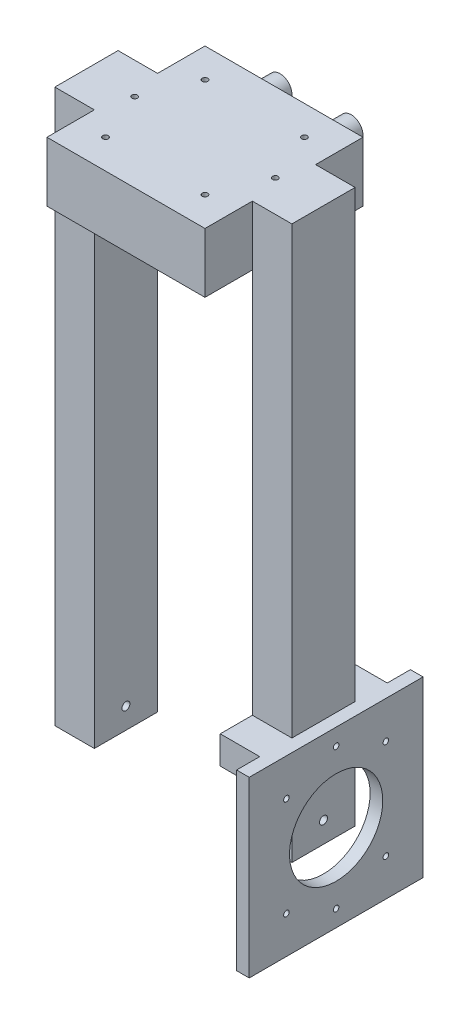
SolidWorks part; units mm, degrees
ref_plane "前视基准面" through (0, 0, 0) normal (0, 0, 1) x (1, 0, 0)
ref_plane "上视基准面" through (0, 0, 0) normal (0, 1, 0) x (1, 0, 0)
ref_plane "右视基准面" through (0, 0, 0) normal (1, 0, 0) x (0, 0, -1)
other "Configuration Table"
sketch "草图1" plane through (0, 0, 0) normal (0, 1, 0) x (1, 0, 0)
  line L1 (-75, 20) -> (75, 20)
  line L2 (-75, 20) -> (-75, -20)
  line L3 (-75, -20) -> (75, -20)
  line L4 (75, 20) -> (75, -20)
  line L5 (-75, 20) -> (75, -20) construction
  line L6 (-75, -20) -> (75, 20) construction
  point P0 (0, 0)
  dimension "D1" = 150
  dimension "D2" = 40
extrude "凸台-拉伸1" add sketch "草图1" along normal blind 350
sketch "草图7" plane through (0, 0, -20) normal (0, 0, -1) x (-1, 0, 0)
  line L1 (0, 0) -> (-50, 0)
  line L2 (0, 0) -> (0, 312.2326)
  line L3 (0, 312.2326) -> (-50, 312.2326)
  line L4 (-50, 0) -> (-50, 312.2326)
  dimension "D1" = 50
extrude "切除-拉伸3" cut sketch "草图7" against normal up to next
mirror "镜向2" about plane through (0, 0, 0) normal (1, 0, 0) of "切除-拉伸3"
sketch "草图8" plane through (-75, 0, 0) normal (-1, 0, 0) x (0, 0, 1)
  circle A0 centre (0, 13.2361) radius 2.5
  dimension "D1" = 5
extrude "切除-拉伸4" cut sketch "草图8" against normal up to next
mirror "镜向3" about plane through (0, 0, 0) normal (1, 0, 0) of "切除-拉伸4"
sketch "草图12" plane through (0, 0, 20) normal (0, 0, 1) x (1, 0, 0)
  line L0 (-75, 350) -> (75, 350) construction
  line L1 (-50, 312.2326) -> (50, 312.2326)
  line L2 (-50, 312.2326) -> (-50, 350)
  line L3 (-50, 350) -> (50, 350)
  line L4 (50, 312.2326) -> (50, 350)
extrude "凸台-拉伸2" add sketch "草图12" along normal mid plane 100 from surface at -20 starting at plane "前视基准面"
sketch "草图14" plane through (0, 350, 0) normal (0, 1, 0) x (1, 0, 0)
  circle A0 centre (0, 0) radius 44.5 construction
  circle A2 centre (-31.4663, -31.4663) radius 1.75
  circle A3 centre (-44.5, 0) radius 1.75
  circle A4 centre (-31.4663, 31.4663) radius 1.75
  circle A6 centre (31.4663, 31.4663) radius 1.75
  circle A7 centre (44.5, 0) radius 1.75
  circle A8 centre (31.4663, -31.4663) radius 1.75
  point P22 (0, 0)
  dimension "D1" = 89
extrude "切除-拉伸7" cut sketch "草图14" against normal blind 25
sketch "草图16" plane through (0, 0, -50) normal (0, 0, -1) x (-1, 0, 0)
  line L0 (-50, 331.1163) -> (50, 331.1163) construction
  line L1 (-50, 312.2326) -> (-50, 350) construction
  line L2 (50, 350) -> (50, 312.2326) construction
  line L3 (0, 331.1163) -> (0, 298.7734) construction
  circle A0 centre (-22.5, 331.1163) radius 7.5
  circle A1 centre (22.5, 331.1163) radius 7.5
  dimension "D1" = 15
  dimension "D2" = 45
extrude "凸台-拉伸3" add sketch "草图16" along normal blind 20
sketch "草图18" plane through (75, 0, 0) normal (1, 0, 0) x (0, 0, -1)
  line L1 (-55, 68.2361) -> (55, 68.2361)
  line L2 (-55, 68.2361) -> (-55, -41.7639)
  line L3 (-55, -41.7639) -> (55, -41.7639)
  line L4 (55, 68.2361) -> (55, -41.7639)
  line L5 (-55, 68.2361) -> (55, -41.7639) construction
  line L6 (-55, -41.7639) -> (55, 68.2361) construction
  point P0 (0, 13.2361)
  dimension "D1" = 110
extrude "凸台-拉伸4" add sketch "草图18" along normal blind 8
sketch "草图19" plane through (83, 0, 0) normal (1, 0, 0) x (0, 0, -1)
  circle A0 centre (0, 13.2361) radius 44.5 construction
  circle A1 centre (0, -31.2639) radius 1.75
  circle A2 centre (-31.4663, -18.2301) radius 1.75
  circle A4 centre (-31.4663, 44.7024) radius 1.75
  circle A5 centre (0, 57.7361) radius 1.75
  circle A6 centre (31.4663, 44.7024) radius 1.75
  circle A8 centre (31.4663, -18.2301) radius 1.75
  circle A9 centre (44.5, 13.2361) radius 1.75 [skipped]
  circle A10 centre (-44.5, 13.2361) radius 1.75 [skipped]
  point P21 (0, 13.2361)
  dimension "D1" = 89
  dimension "D2" = 3.5
  dimension "D3" = 8
extrude "切除-拉伸8" cut sketch "草图19" against normal blind 8
sketch "草图20" plane through (83, 0, 0) normal (1, 0, 0) x (0, 0, -1)
  circle A0 centre (0, 13.2361) radius 29.5
  dimension "D1" = 59
extrude "切除-拉伸9" cut sketch "草图20" against normal blind 8
sketch "草图21" plane through (75, 0, 0) normal (-1, 0, 0) x (0, 0, 1)
  line L1 (-40.3474, 50.5173) -> (-20, 50.5173)
  line L2 (-40.3474, 50.5173) -> (-40.3474, 68.2361)
  line L3 (-40.3474, 68.2361) -> (-20, 68.2361)
  line L4 (-20, 50.5173) -> (-20, 68.2361)
extrude "凸台-拉伸5" add sketch "草图21" along normal up to surface (25 mm away) up to face at (50, 13.2361, -2.5)
sketch "草图23" plane through (50, 0, 0) normal (-1, 0, 0) x (0, 0, 1)
  line L0 (0, 0) -> (0, 238.3877) construction
ref_plane "基准面1" through (0, 0, 0) normal (0, 0, 1) x (0, 1, 0)
mirror "镜向4" about plane through (0, 0, 0) normal (0, 0, 1) of "凸台-拉伸5"
